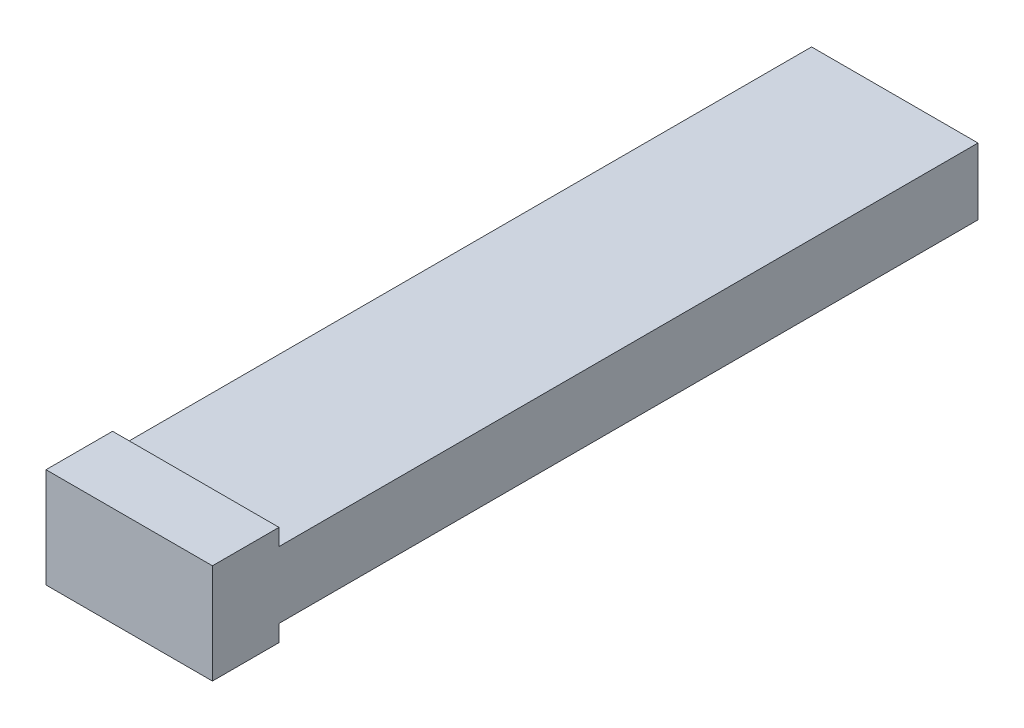
SolidWorks part; units mm, degrees
ref_plane "Plan de face" through (0, 0, 0) normal (0, 0, 1) x (1, 0, 0)
ref_plane "Plan de dessus" through (0, 0, 0) normal (0, 1, 0) x (1, 0, 0)
ref_plane "Plan de droite" through (0, 0, 0) normal (1, 0, 0) x (0, 0, -1)
sketch "Esquisse1" plane through (0, 0, 0) normal (0, 0, 1) x (1, 0, 0)
  line L1 (-2.5, -1) -> (2.5, -1)
  line L2 (-2.5, -1) -> (-2.5, 1)
  line L3 (-2.5, 1) -> (2.5, 1)
  line L4 (2.5, -1) -> (2.5, 1)
  line L5 (-2.5, -1) -> (2.5, 1) construction
  line L6 (-2.5, 1) -> (2.5, -1) construction
  point P0 (0, 0)
  dimension "D1" = 2
  dimension "D2" = 5
extrude "Boss.-Extru.1" add sketch "Esquisse1" along normal blind 21
sketch "Esquisse2" plane through (0, 0, 21) normal (0, 0, 1) x (1, 0, 0)
  line L1 (-2.5, -1.5) -> (2.5, -1.5)
  line L2 (-2.5, -1.5) -> (-2.5, 1.5)
  line L3 (-2.5, 1.5) -> (2.5, 1.5)
  line L4 (2.5, -1.5) -> (2.5, 1.5)
  line L5 (-2.5, -1.5) -> (2.5, 1.5) construction
  line L6 (-2.5, 1.5) -> (2.5, -1.5) construction
  dimension "D1" = 5
  dimension "D2" = 3
extrude "Boss.-Extru.2" add sketch "Esquisse2" along normal blind 2
